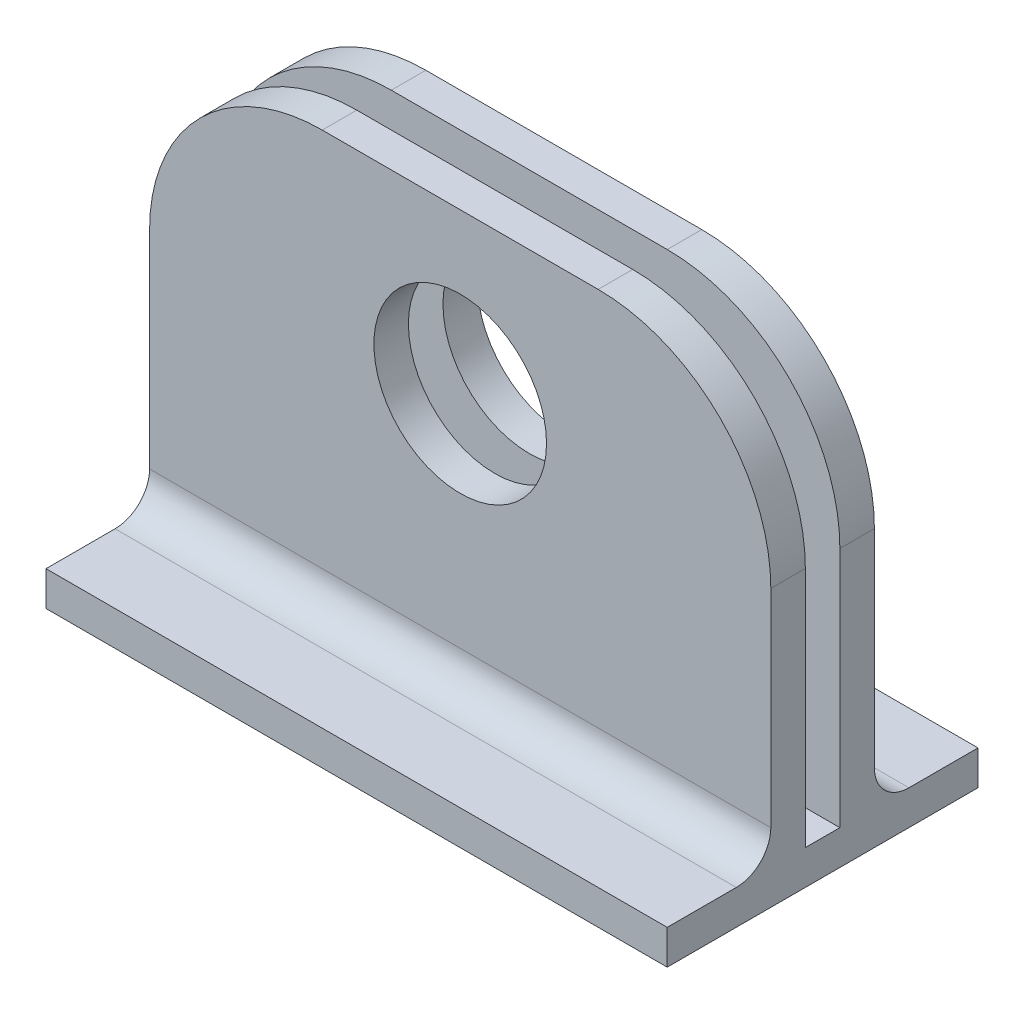
SolidWorks part; units mm, degrees
ref_plane "Front Plane" through (0, 0, 0) normal (0, 0, 1) x (1, 0, 0)
ref_plane "Top Plane" through (0, 0, 0) normal (0, 1, 0) x (1, 0, 0)
ref_plane "Right Plane" through (0, 0, 0) normal (1, 0, 0) x (0, 0, -1)
sketch "Sketch1" plane through (0, 0, 0) normal (0, 0, 1) x (1, 0, 0)
  line L1 (0, 0) -> (35.9808, 0)
  line L2 (0, 0) -> (0, 26)
  line L3 (0, 26) -> (35.9808, 26)
  line L4 (35.9808, 0) -> (35.9808, 26)
  dimension "D1" = 26
extrude "Boss-Extrude1" add sketch "Sketch1" along normal blind 2
pattern_linear "LPattern1" count 2 spacing 4 along (0, 0, 1) of "Boss-Extrude1"
sketch "Sketch2" plane through (0, 0, 0) normal (0, 0, -1) x (-1, 0, 0)
  line L0 (0, 26) -> (0, 0) construction
  line L1 (-35.9808, 0) -> (0, 0)
  line L2 (-35.9808, 0) -> (-35.9808, 2)
  line L3 (-35.9808, 2) -> (0, 2)
  line L4 (0, 0) -> (0, 2)
  dimension "D1" = 2
extrude "Boss-Extrude2" add sketch "Sketch2" along normal blind 6 and the other way blind 12
fillet "Fillet1" radius 2 2 edges at (17.9904, 2, 0) (17.9904, 2, 6)
fillet "Fillet2" radius 10 4 edges at (35.9808, 26, 1) (0, 26, 5) (35.9808, 26, 5) (0, 26, 1)
sketch "Sketch4" plane through (0, 0, 6) normal (0, 0, 1) x (1, 0, 0)
  circle A0 centre (17.9904, 16.77) radius 5
  dimension "D1" = 10
extrude "Cut-Extrude1" cut sketch "Sketch4" against normal blind 6
